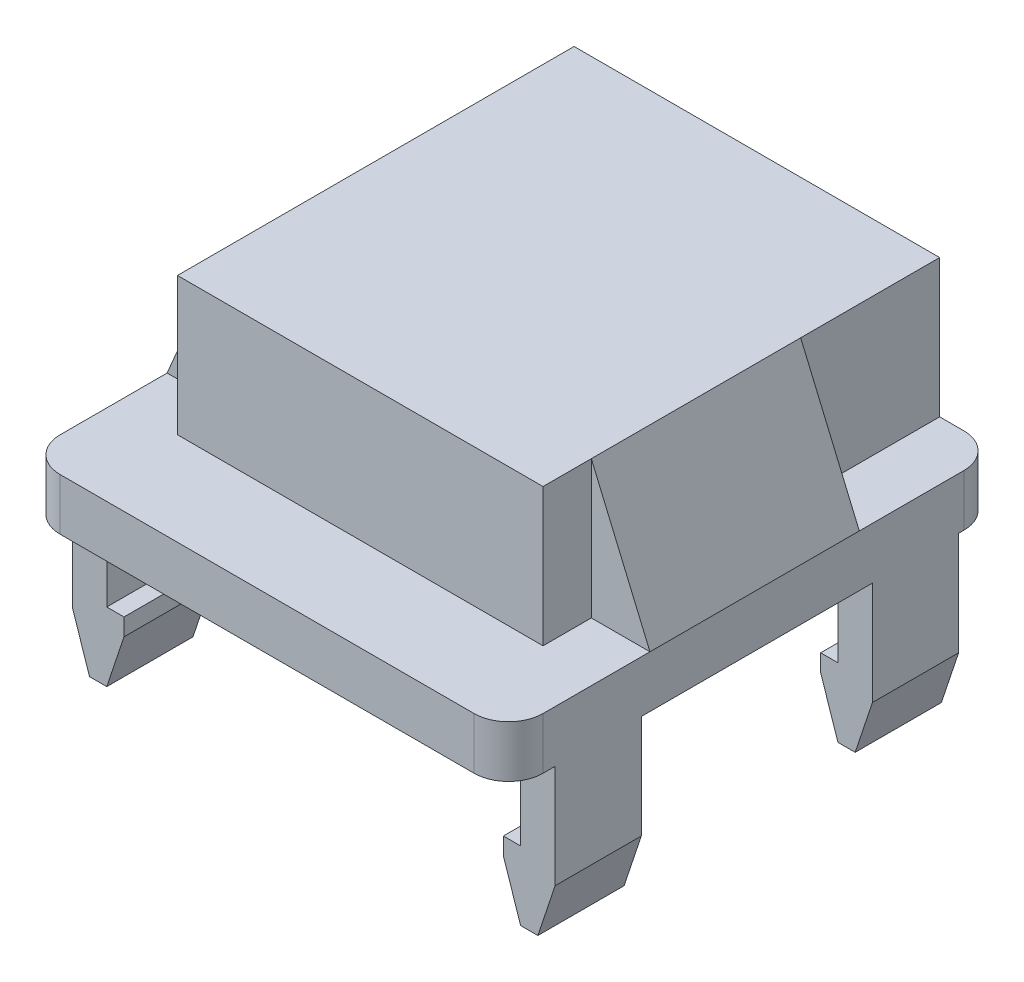
SolidWorks part; units mm, degrees
ref_plane "Front Plane" through (0, 0, 0) normal (0, 0, 1) x (1, 0, 0)
ref_plane "Top Plane" through (0, 0, 0) normal (0, 1, 0) x (1, 0, 0)
ref_plane "Right Plane" through (0, 0, 0) normal (1, 0, 0) x (0, 0, -1)
sketch "Sketch1" plane through (0, 0, 0) normal (0, 1, 0) x (1, 0, 0)
  line L1 (-6, -7.1) -> (6, -7.1)
  line L2 (-7, -6.1) -> (-7, 6.1)
  line L3 (-6, 7.1) -> (6, 7.1)
  line L4 (7, -6.1) -> (7, 6.1)
  line L5 (-7, -7.1) -> (7, 7.1) construction
  line L6 (-7, 7.1) -> (7, -7.1) construction
  arc A0 (-6, -7.1) -> (-7, -6.1) centre (-6, -6.1) cw
  arc A1 (6, -7.1) -> (7, -6.1) centre (6, -6.1) ccw
  arc A2 (6, 7.1) -> (7, 6.1) centre (6, 6.1) cw
  arc A3 (-7, 6.1) -> (-6, 7.1) centre (-6, 6.1) cw
  point P0 (0, 0)
  dimension "D3" = 1
  dimension "D1" = 14
  dimension "D2" = 14.2
extrude "Boss-Extrude1" add sketch "Sketch1" along normal blind 1.5
sketch "Sketch2" plane through (0, 1.5, 0) normal (0, 1, 0) x (1, 0, 0)
  line L1 (-5.3, -4.4) -> (5.3, -4.4)
  line L2 (-5.3, -4.4) -> (-5.3, 7.1)
  line L3 (-5.3, 7.1) -> (5.3, 7.1)
  line L4 (5.3, -4.4) -> (5.3, 7.1)
  line L7 (-7, 6.1) -> (-7, -6.1) construction
  line L8 (7, -6.1) -> (7, 6.1) construction
  point P0 (0, 0)
  point P6 (0, 0)
  point P9 (0.4539, 7.1)
  point P10 (0.4539, 7.1)
  point P11 (-1.3124, 6.4453)
  point P12 (0.4539, 7.1)
  point P13 (0.4539, 7.1)
  point P14 (5.3, 3.7727)
  dimension "D1" = 10.6
  dimension "D2" = 11.5
  dimension "D3" = 1.7
  dimension "D4" = 1.7
extrude "Boss-Extrude2" add sketch "Sketch2" along normal blind 4
ref_plane "Plane3" through (0, 0, 3) normal (0, 0, 1) x (1, 0, 0)
sketch "Sketch4" plane through (0, 0, 3) normal (0, 0, 1) x (1, 0, 0)
  line L0 (-5.3, 5.5) -> (-7, 1.5)
  line L1 (-7, 1.5) -> (-5.3, 1.5)
  line L2 (-5.3, 1.5) -> (-5.3, 5.5)
  line L3 (5.3, 5.5) -> (7, 1.5)
  line L4 (7, 1.5) -> (5.3, 1.5)
  line L5 (5.3, 1.5) -> (5.3, 5.5)
extrude "Boss-Extrude4" add sketch "Sketch4" against normal blind 6.07
sketch "Sketch5" plane through (0, 0, 0) normal (0, -1, 0) x (1, 0, 0)
  line L0 (-7, -6.1) -> (-7, 6.1) construction
  line L1 (-7, 5.75) -> (-5.5, 5.75)
  line L2 (-7, 5.75) -> (-7, 3.25)
  line L3 (-7, 3.25) -> (-5.5, 3.25)
  line L4 (-5.5, 5.75) -> (-5.5, 3.25)
  line L5 (-6, 7.1) -> (6, 7.1) construction
  line L6 (0, 7.1) -> (0, -7.1)
  line L7 (-7, -3.45) -> (-5.5, -3.45)
  line L8 (-7, -3.45) -> (-7, -5.95)
  line L9 (-7, -5.95) -> (-5.5, -5.95)
  line L10 (-5.5, -3.45) -> (-5.5, -5.95)
  line L11 (6, -7.1) -> (-6, -7.1) construction
  line L12 (7, -5.95) -> (5.5, -5.95)
  line L13 (5.5, -3.45) -> (5.5, -5.95)
  line L14 (7, -3.45) -> (7, -5.95)
  line L15 (7, -3.45) -> (5.5, -3.45)
  line L16 (7, 3.25) -> (5.5, 3.25)
  line L17 (5.5, 5.75) -> (5.5, 3.25)
  line L18 (7, 5.75) -> (7, 3.25)
  line L19 (7, 5.75) -> (5.5, 5.75)
  line M10 (-7, 6.1) -> (-7, -6.1)
  line M14 (7, -6.1) -> (7, 6.1)
  dimension "D1" = 1.35
  dimension "D2" = 2.5
  dimension "D3" = 1.5
  dimension "D4" = 6.7
  dimension "D5" = 2.5
  dimension "D6" = 1.5
extrude "Boss-Extrude5" add sketch "Sketch5" along normal blind 4.5 contours L4 L1 L3 M10 | L10 L7 L9 M10 | L15 L13 L12 M14 | L19 L17 L16 M14
sketch "Sketch6" plane through (0, 0, 5.75) normal (0, 0, 1) x (1, 0, 0)
  line L0 (-5.5, -4.5) -> (-5.5, 0) construction
  line L1 (-5.5, 0) -> (-6, 0)
  line L2 (-5.5, 0) -> (-5.5, -2.5)
  line L3 (-5.5, -2.5) -> (-6, -2.5)
  line L4 (-6, 0) -> (-6, -2.5)
  line L5 (-5.5, -3) -> (-6, -4.5)
  line L6 (-7, -4.5) -> (-5.5, -4.5) construction
  line L7 (-5.5, -3) -> (-5.5, -4.5)
  line L8 (-5.5, -4.5) -> (-6, -4.5)
  line L9 (-7, -4.5) -> (-7, -3)
  line L10 (-7, -4.5) -> (-7, 0) construction
  line L11 (-7, -3) -> (-6.5, -4.5)
  line L12 (-6.5, -4.5) -> (-7, -4.5)
  line L13 (0, 0) -> (0, 6.5092)
  line L14 (-6, 0) -> (6, 0) construction
  line L15 (7, -4.5) -> (7, -3)
  line L16 (6.5, -4.5) -> (7, -4.5)
  line L17 (7, -3) -> (6.5, -4.5)
  line L18 (5.5, -4.5) -> (6, -4.5)
  line L19 (5.5, -3) -> (6, -4.5)
  line L20 (5.5, -3) -> (5.5, -4.5)
  line L21 (5.5, -2.5) -> (6, -2.5)
  line L22 (5.5, 0) -> (5.5, -2.5)
  line L23 (5.5, 0) -> (6, 0)
  line L24 (6, 0) -> (6, -2.5)
  line M12 (-5.5, 0) -> (-7, 0)
  line M15 (-5.5, -4.5) -> (-5.5, 0)
  dimension "D1" = 0.5
  dimension "D2" = 0
  dimension "D3" = 0.5
  dimension "D4" = 1.5
  dimension "D5" = 0.5
  dimension "D6" = 2.5
extrude "Cut-Extrude1" cut sketch "Sketch6" against normal through all contours L4 L3 M12 M15 | L9 L11 L12 | L5 L8 L7 | L24 L21 L22 L23 | L19 L18 L20 | L15 L17 L16
sketch "Sketch7" plane through (0, 1.5, 0) normal (0, 1, 0) x (1, 0, 0)
  line L0 (-0.825, -3) -> (0.825, -3) construction
  line L1 (-6.3951, -3) -> (-5.3, -3)
  line L2 (-6.3951, -3) -> (-6.3951, -5.69)
  line L3 (-6.3951, -5.69) -> (-5.3, -5.69)
  line L4 (-5.3, -3) -> (-5.3, -5.69)
  line L5 (-6, -3.25) -> (-6, -5.75) construction
  line L6 (-6.3951, -3.34) -> (-5.3, -3.34)
  line L7 (-5.3, -3.34) -> (-2.5459, -2.8132)
  line L8 (-6.1119, -3) -> (-6.1179, -3.34)
  line L9 (-5.3, 7.1) -> (-5.3, 3.07) construction
  line L10 (-5.3, 3.5799) -> (-6.3951, 3.5799)
  line L11 (-5.3, 3.5799) -> (-5.3, 5.9299)
  line L12 (-5.3, 5.9299) -> (-6.3951, 5.9299)
  line L13 (-6.3951, 3.5799) -> (-6.3951, 5.9299)
  line L14 (0, 0) -> (0, 6.6252)
  line L15 (5.3, -3) -> (5.3, -5.69)
  line L16 (6.3951, -5.69) -> (5.3, -5.69)
  line L17 (6.3951, -3) -> (6.3951, -5.69)
  line L18 (6.3951, -3.34) -> (5.3, -3.34)
  line L19 (5.3, 3.5799) -> (6.3951, 3.5799)
  line L20 (5.3, 3.5799) -> (5.3, 5.9299)
  line L21 (6.3951, 3.5799) -> (6.3951, 5.9299)
  line L22 (5.3, 5.9299) -> (6.3951, 5.9299)
  dimension "D1" = 0.7
  dimension "D2" = 1.0951
  dimension "D3" = 0.34
  dimension "D4" = 2.35
  dimension "D5" = 2.35
